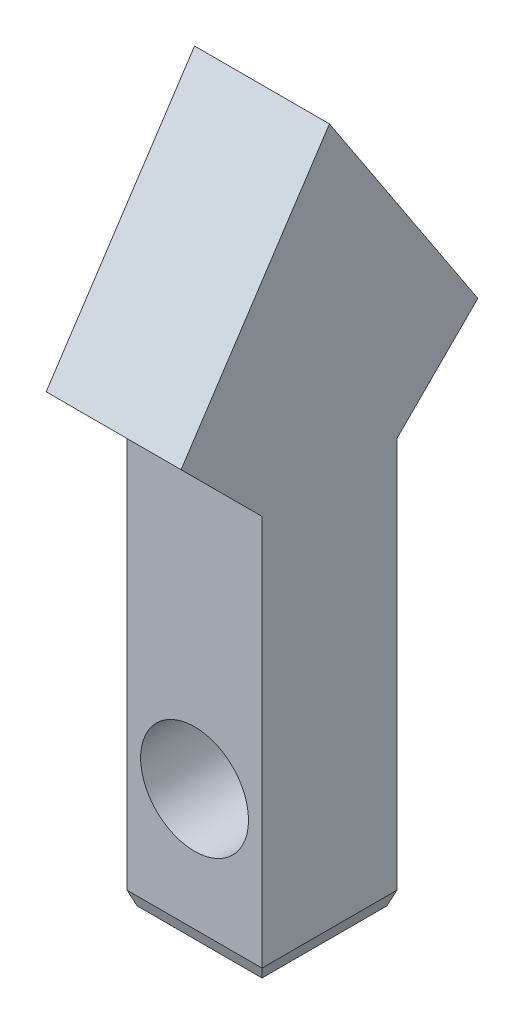
SolidWorks part; units mm, degrees
ref_plane "Front Plane" through (0, 0, 0) normal (1, 0, 0) x (0, 1, 0)
ref_plane "Top Plane" through (0, 0, 0) normal (0, 0, 1) x (0, 1, 0)
ref_plane "Right Plane" through (0, 0, 0) normal (0, 1, 0) x (-1, 0, 0)
sketch "Sketch2" plane through (0, 0, 0) normal (1, 0, 0) x (0, 1, 0)
  line L3 (-3, 8) -> (-13, 8)
  line L4 (-13, 8) -> (-13, 3)
  line L5 (-13, 3) -> (-3, 3)
  line L7 (-3, 3) -> (-3, -0.4126) construction
  line L10 (-13, 5.5) -> (12.8743, 5.5) construction
  line L11 (0, 11) -> (0, -6.0715) construction
  line L14 (5, 11) -> (13.3516, 5.5)
  line L15 (-13, 0.5) -> (-13, 10.5) construction
  line L16 (13.3516, 5.5) -> (5, 0)
  line L19 (2, 8) -> (5, 11)
  line L20 (2, 3) -> (5, 0)
  line L21 (-3, 8) -> (2, 8)
  line L22 (-3, 3) -> (2, 3)
  dimension "D1" = 5
  dimension "D2" = 13
extrude "Boss-Extrude1" add sketch "Sketch2" along normal blind 5
sketch "Sketch4" plane through (0, 0, 8) normal (0, 0, 1) x (1, 0, 0)
  line L0 (2.5, -3) -> (2.5, -13) construction
  line L2 (5, -13) -> (0, -13) construction
  line L3 (2.5, -6) -> (2.5, -10) construction
  line L4 (0.5, -8) -> (4.5, -8) construction
  circle A0 centre (2.5, -8) radius 2
  dimension "D1" = 4
extrude "Cut-Extrude2" cut sketch "Sketch4" against normal blind 10
chamfer "Chamfer1" distance 0.5 angle 20 4 edges at (5, -13, 5.5) (2.5, -13, 3) (0, -13, 5.5) (2.5, -13, 8)
